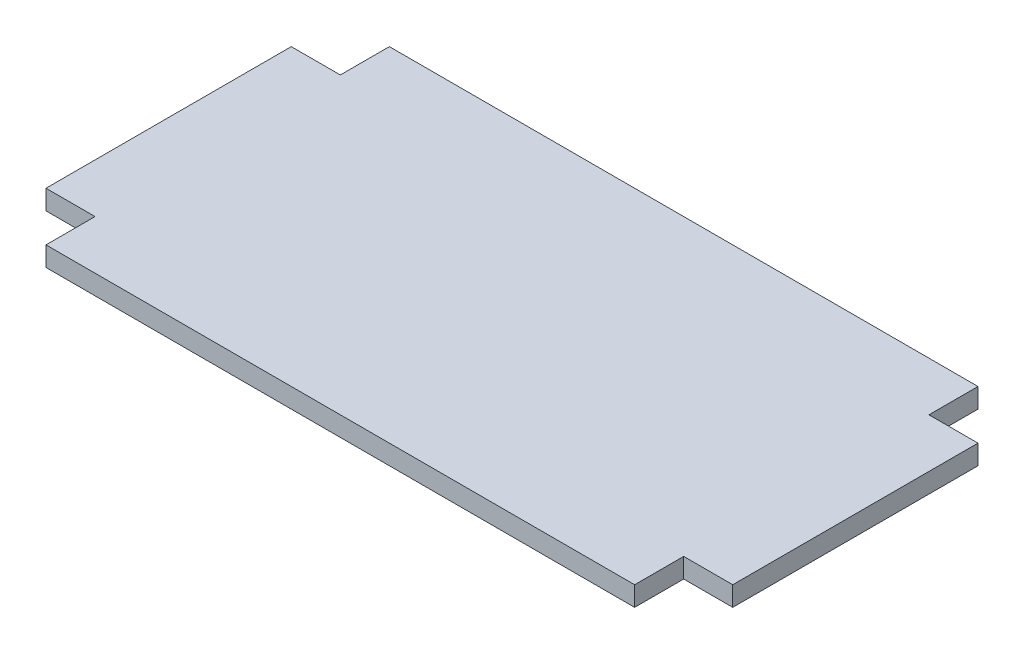
SolidWorks part; units mm, degrees
ref_plane "Płaszczyzna przednia" through (0, 0, 0) normal (0, 0, 1) x (1, 0, 0)
ref_plane "Płaszczyzna górna" through (0, 0, 0) normal (0, 1, 0) x (1, 0, 0)
ref_plane "Płaszczyzna prawa" through (0, 0, 0) normal (1, 0, 0) x (0, 0, -1)
sketch "Szkic1" plane through (0, 0, 0) normal (0, 1, 0) x (1, 0, 0)
  line L0 (0, 35) -> (0, -35) construction
  line L1 (-60, -35) -> (60, -35)
  line L2 (-70, -25) -> (-70, 25)
  line L3 (-60, 35) -> (60, 35)
  line L4 (70, -25) -> (70, 25)
  line L5 (-70, 0) -> (70, 0) construction
  line L6 (70, 25) -> (60, 25)
  line L9 (70, -25) -> (60, -25)
  line L10 (60, -35) -> (60, -25)
  line L11 (60, 35) -> (60, 25)
  line L15 (-60, 35) -> (-60, 25)
  line L16 (-70, 25) -> (-60, 25)
  line L18 (-70, -25) -> (-60, -25)
  line L19 (-60, -35) -> (-60, -25)
  point P0 (155.266, 17.0427)
  point P1 (0, 0)
  dimension "D1" = 50
  dimension "D2" = 120
  dimension "D3" = 10
  dimension "D4" = 10
extrude "Dodanie-wyciągnięcie1" add sketch "Szkic1" along normal blind 4
